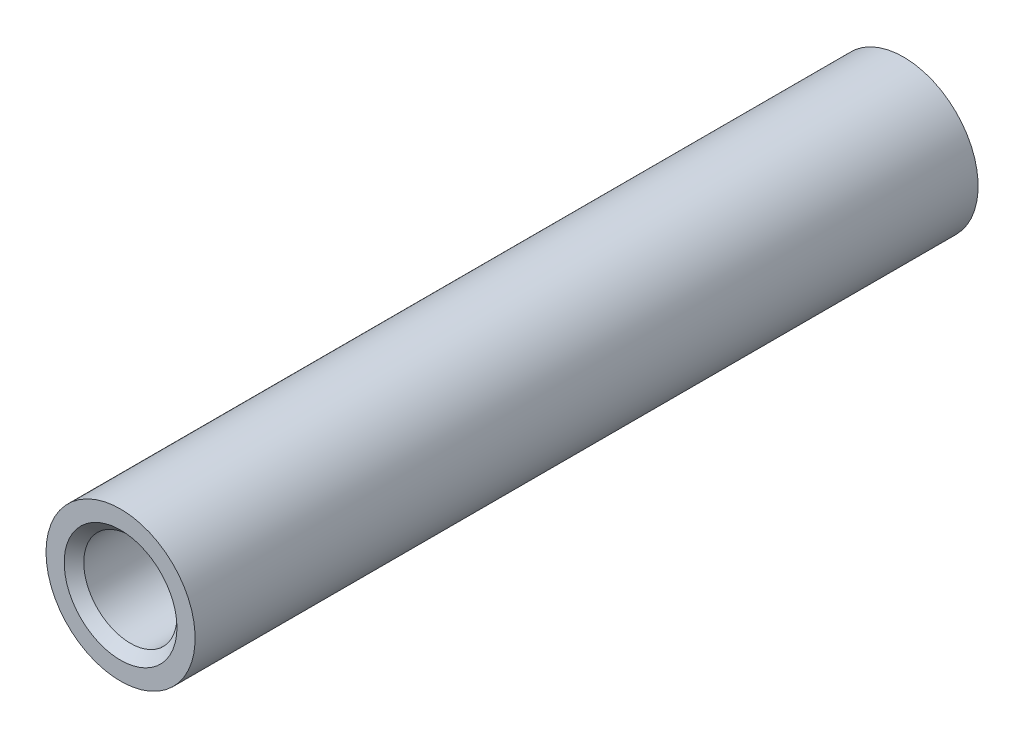
SolidWorks part; units mm, degrees
ref_plane "Plano frontal" through (0, 0, 0) normal (0, 0, 1) x (1, 0, 0)
ref_plane "Plano superior" through (0, 0, 0) normal (0, 1, 0) x (1, 0, 0)
ref_plane "Plano direito" through (0, 0, 0) normal (1, 0, 0) x (0, 0, -1)
sketch "Esboço1" plane through (0, 0, 0) normal (0, 0, 1) x (1, 0, 0)
  circle A0 centre (0, 0) radius 4
  dimension "D1" = 8
extrude "Ressalto-extrusão1" add sketch "Esboço1" along normal mid plane 42
hole_wizard "Furo roscado de M61" positions "Esboço2" profile "Esboço3" tap size "M6" standard "DIN"
sketch "Esboço2" plane through (0, 0, 21) normal (0, 0, 1) x (1, 0, 0)
  point P0 (0, 0)
sketch "Esboço3" plane through (0, 0, 21) normal (1, 0, 0) x (0, -1, 0)
  line L0 (0, 0) -> (0, 16.5022)
  line L1 (0, 16.5022) -> (2.5, 15)
  line L2 (2.5, 15) -> (2.5, 0.525)
  line L3 (2.5, 0.525) -> (3.025, 0)
  line L5 (3.025, 0) -> (0, 0)
  line L6 (-2.5, 0.525) -> (-3.025, 0) construction
  line L10 (0, 16.5022) -> (-2.5, 15) construction
  line L11 (0, -6.35) -> (0, 107.95) construction
  dimension "Tap Drill Dia." = 5
  dimension "Tap Drill Depth" = 15
  dimension "Near C'Sink Dia." = 6.05
  dimension "Near C'Sink Angle" = 90
  dimension "Drill Angle" = 118
cosmetic thread "Rosca de furo1" parameters "D1"=12, "D2"=6
mirror "Espelhar2" about plane through (0, 0, 0) normal (0, 0, 1) of "Furo roscado de M61"
